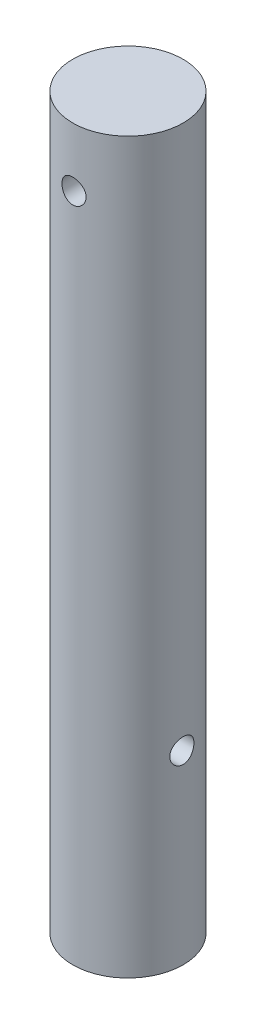
SolidWorks part; units mm, degrees
ref_plane "Front Plane" through (0, 0, 0) normal (0, 0, 1) x (1, 0, 0)
ref_plane "Top Plane" through (0, 0, 0) normal (0, 1, 0) x (1, 0, 0)
ref_plane "Right Plane" through (0, 0, 0) normal (1, 0, 0) x (0, 0, -1)
sketch "Sketch1" plane through (0, 0, 0) normal (0, 1, 0) x (1, 0, 0)
  circle A0 centre (0, 0) radius 4.7625
  dimension "D1" = 9.525
extrude "Boss-Extrude1" add sketch "Sketch1" against normal blind 9.525
sketch "Sketch2" plane through (0, -9.525, 0) normal (0, -1, 0) x (-1, 0, 0)
  circle A0 centre (0, 0) radius 4.7625
  dimension "D1" = 9.525
extrude "Boss-Extrude2" add sketch "Sketch2" along normal blind 53.34
sketch "Sketch3" plane through (0, 0, 0) normal (0, 0, 1) x (1, 0, 0)
  circle A0 centre (0, -5.08) radius 1.0414
  point P2 (0, 0)
  dimension "D1" = 2.0828
  dimension "D2" = 5.08
extrude "Cut-Extrude1" cut sketch "Sketch3" against normal up to surface and the other way up to surface up to face at (0, 0, 4.7625) other way up to face at (0, 0, 4.7625)
sketch "Sketch4" plane through (0, 0, 0) normal (1, 0, 0) x (0, 0, -1)
  line L0 (-4.7625, -62.865) -> (4.7625, -62.865) construction
  circle A0 centre (0, -46.863) radius 1.0414
  point P2 (0, 0)
  dimension "D1" = 2.0828
  dimension "D2" = 16.002
extrude "Cut-Extrude2" cut sketch "Sketch4" against normal up to surface and the other way up to surface up to face at (1.0196, -4.8679, 4.6521) other way up to face at (1.0196, -4.8679, 4.6521)
